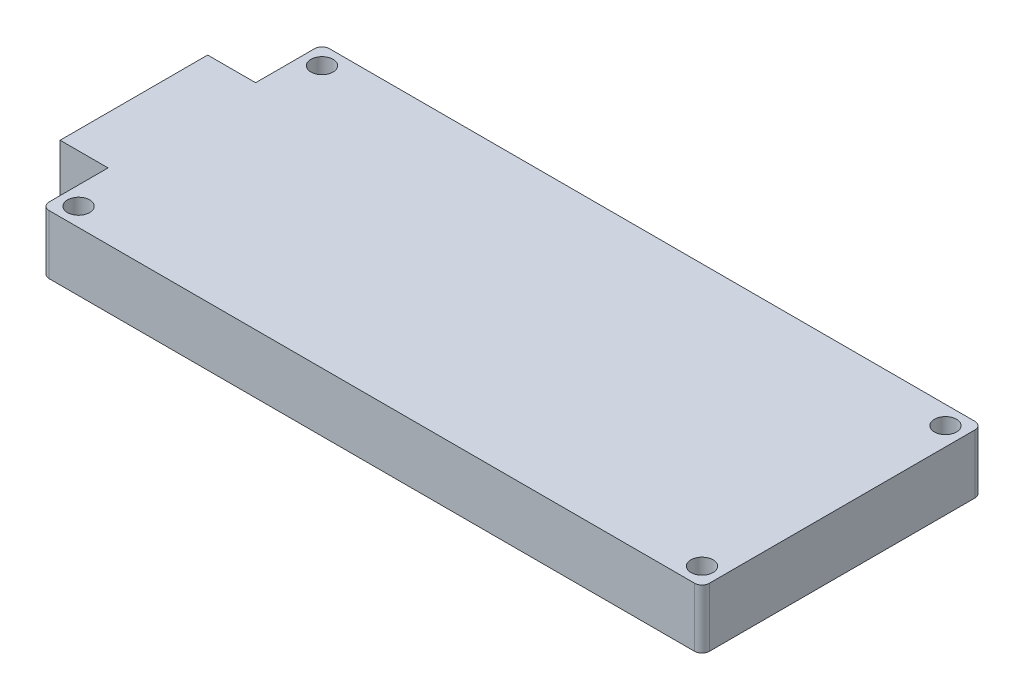
SolidWorks part; units mm, degrees
ref_plane "Front Plane" through (0, 0, 0) normal (0, 0, 1) x (1, 0, 0)
ref_plane "Top Plane" through (0, 0, 0) normal (0, 1, 0) x (1, 0, 0)
ref_plane "Right Plane" through (0, 0, 0) normal (1, 0, 0) x (0, 0, -1)
sketch "Sketch1" plane through (0, 0, 0) normal (0, 1, 0) x (1, 0, 0)
  line L1 (-44.75, 19) -> (44.75, 19)
  line L2 (-44.75, 19) -> (-44.75, -19)
  line L3 (-44.75, -19) -> (44.75, -19)
  line L4 (44.75, 19) -> (44.75, -19)
  line L5 (-44.75, 19) -> (44.75, -19) construction
  line L6 (-44.75, -19) -> (44.75, 19) construction
  point P0 (0, 0)
  dimension "D1" = 38
  dimension "D2" = 89.5
extrude "Boss-Extrude1" add sketch "Sketch1" along normal blind 8
sketch "Sketch2" plane through (0, 8, 0) normal (0, 1, 0) x (1, 0, 0)
  line L0 (-42.25, 19) -> (-42.25, 16.5) construction
  line L1 (-42.25, 16.5) -> (42.25, 16.5) construction
  line L2 (-42.25, 16.5) -> (-42.25, -16.5) construction
  line L3 (-42.25, -16.5) -> (42.25, -16.5) construction
  line L4 (42.25, 16.5) -> (42.25, -16.5) construction
  line L5 (42.25, -19) -> (42.25, -16.5) construction
  line L6 (-44.75, -19) -> (44.75, -19) construction
  line L7 (44.75, 19) -> (-44.75, 19) construction
  line L8 (-42.25, 16.5) -> (-44.75, 16.5) construction
  line L9 (-44.75, 19) -> (-44.75, -19) construction
  line L10 (42.25, -16.5) -> (44.75, -16.5) construction
  line L11 (44.75, -19) -> (44.75, 19) construction
  circle A0 centre (-42.25, 16.5) radius 1.5
  circle A1 centre (42.25, 16.5) radius 1.5
  circle A2 centre (42.25, -16.5) radius 1.5
  circle A3 centre (-42.25, -16.5) radius 1.5
  point P0 (0, 0)
  dimension "D2" = 3
  dimension "D1" = 2.5
extrude "Cut-Extrude1" cut sketch "Sketch2" against normal through all
fillet "Fillet1" radius 1 4 edges at (44.75, 4, -19) (44.75, 4, 19) (-44.75, 4, 19) (-44.75, 4, -19)
sketch "Sketch4" plane through (0, 8, 0) normal (0, 1, 0) x (1, 0, 0)
  line L0 (-44.75, 18) -> (-44.75, -18) construction
  line L1 (-44.75, 10) -> (-51.25, 10)
  line L2 (-44.75, 10) -> (-44.75, -10)
  line L3 (-44.75, -10) -> (-51.25, -10)
  line L4 (-51.25, 10) -> (-51.25, -10)
  point P6 (-44.75, 40.9727)
  point P7 (-44.75, 0)
  point P8 (-60.1709, 10)
  dimension "D1" = 20
  dimension "D2" = 6.5
extrude "Boss-Extrude2" add sketch "Sketch4" against normal up to surface (8 mm away) up to face at (-42.25, 0, 18)
